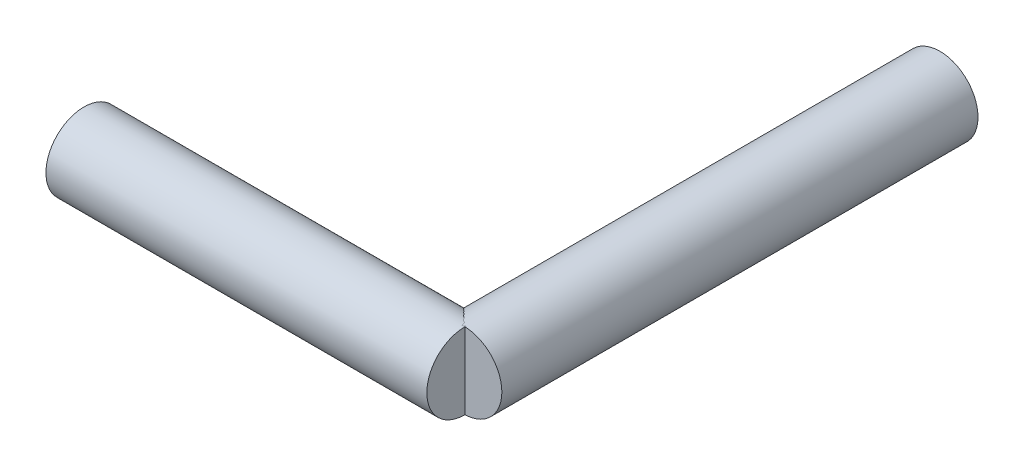
SolidWorks part; units mm, degrees
material "ABS PC"
ref_plane "Ebene vorne" through (0, 0, 0) normal (1, 0, 0) x (0, 1, 0)
ref_plane "Ebene oben" through (0, 0, 0) normal (0, 0, 1) x (0, 1, 0)
ref_plane "Ebene rechts" through (0, 0, 0) normal (0, 1, 0) x (-1, 0, 0)
sketch "Skizze3" plane through (0, 0, 0) normal (1, 0, 0) x (0, 1, 0)
  circle A0 centre (0, 0) radius 8
extrude "Motorarm" add sketch "Skizze3" along normal blind 80
sketch "Skizze4" plane through (0, 0, 0) normal (0, 0, 1) x (0, 1, 0)
  line L0 (0, -8.8) -> (0, 8.8) construction
  circle A0 centre (0, -79.7569) radius 8
extrude "Pendelarm" add sketch "Skizze4" against normal blind 100 separate body
